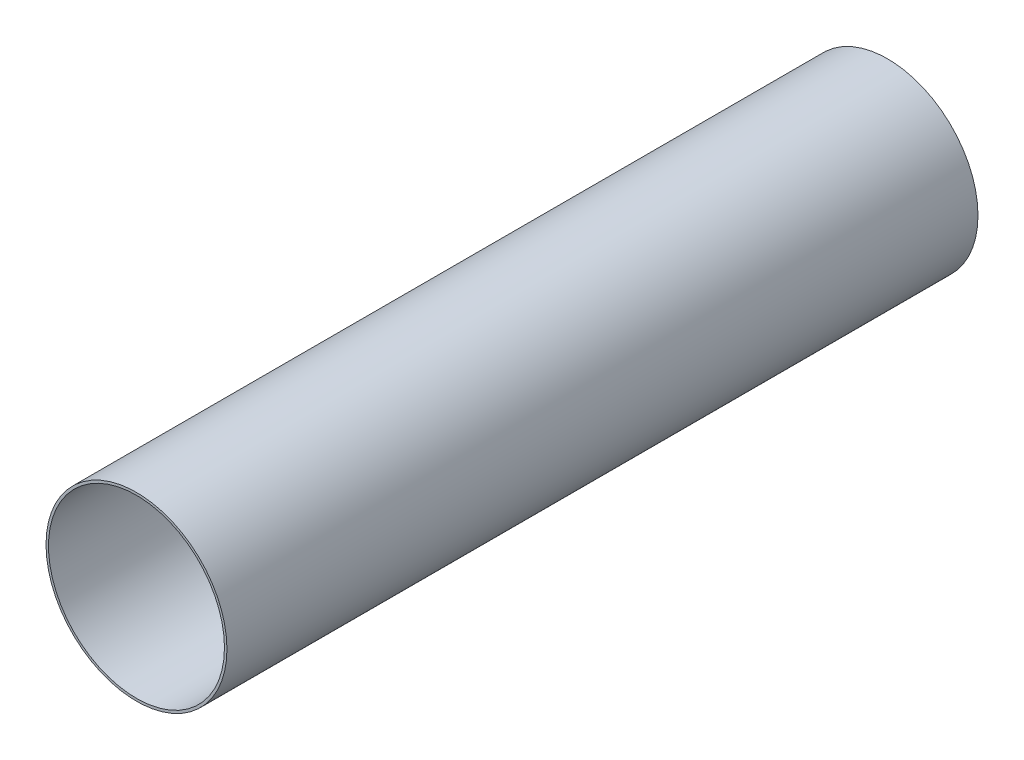
SolidWorks part; units mm, degrees
material "PVC Rigid"
ref_plane "Front Plane" through (0, 0, 0) normal (0, 0, 1) x (1, 0, 0)
ref_plane "Top Plane" through (0, 0, 0) normal (0, 1, 0) x (1, 0, 0)
ref_plane "Right Plane" through (0, 0, 0) normal (1, 0, 0) x (0, 0, -1)
sketch "Sketch1" plane through (0, 0, 0) normal (0, 0, 1) x (1, 0, 0)
  circle A0 centre (0, 0) radius 71
  circle A1 centre (0, 0) radius 73
  dimension "D1" = 142
  dimension "D2" = 146
extrude "Boss-Extrude1" add sketch "Sketch1" along normal blind 604
sketch "Sketch2" plane through (0, 0, 0) normal (0, 0, -1) x (-1, 0, 0)
  circle A0 centre (0, 0) radius 73 construction
  circle A1 centre (0, 0) radius 73
extrude "Boss-Extrude2" add sketch "Sketch2" along normal blind 2
